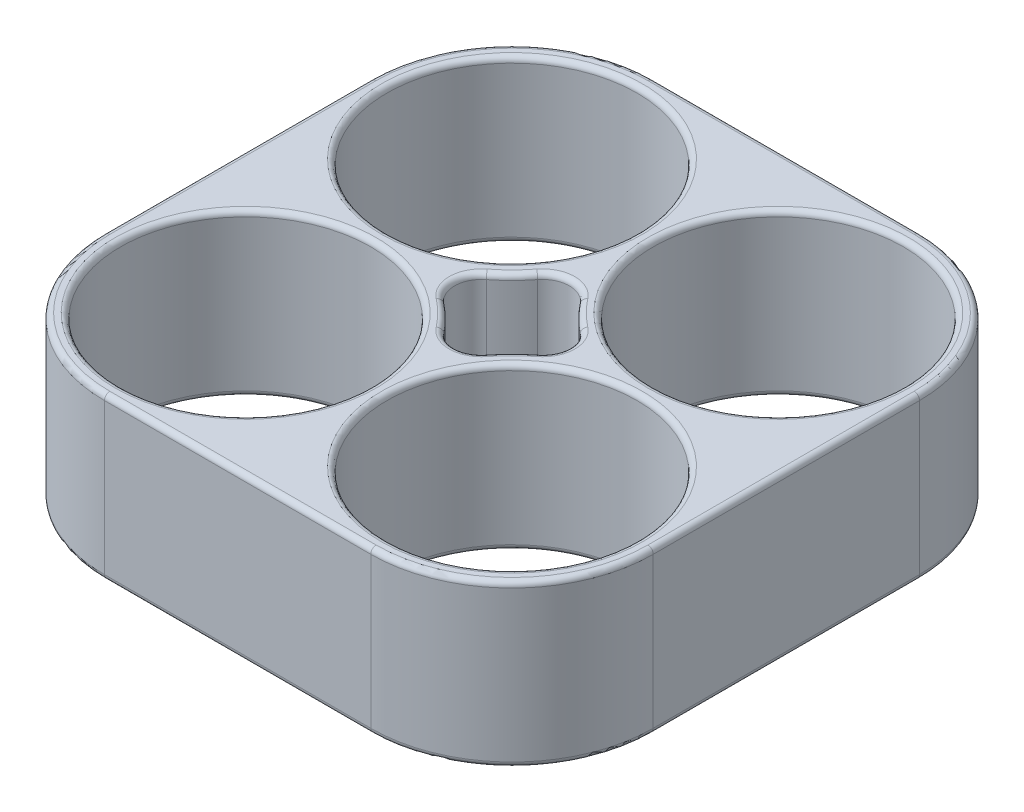
SolidWorks part; units mm, degrees
ref_plane "Front Plane" through (0, 0, 0) normal (0, 0, 1) x (1, 0, 0)
ref_plane "Top Plane" through (0, 0, 0) normal (0, 1, 0) x (1, 0, 0)
ref_plane "Right Plane" through (0, 0, 0) normal (1, 0, 0) x (0, 0, -1)
sketch "Esquisse1" plane through (0, 0, 0) normal (0, 1, 0) x (1, 0, 0)
  line L0 (0, 0) -> (19.8, 0) construction
  line L1 (0, 0) -> (0, 19.8) construction
  line L2 (19.8, 0) -> (19.8, 19.8) construction
  line L3 (-10.5, 19.8) -> (-10.5, 0)
  line L4 (0, 30.3) -> (19.8, 30.3)
  line L5 (30.3, 19.8) -> (30.3, 0)
  line L6 (0, -10.5) -> (19.8, -10.5)
  circle A0 centre (0, 0) radius 9.3
  arc A1 (-10.5, 0) -> (0, -10.5) centre (0, 0) ccw
  circle A2 centre (0, 19.8) radius 9.3
  arc A3 (6.4105, 11.484) -> (8.316, 13.3895) centre (0, 19.8) ccw
  circle A4 centre (19.8, 0) radius 9.3
  arc A5 (13.3895, 8.316) -> (11.484, 6.4105) centre (19.8, 0) ccw
  circle A6 centre (19.8, 19.8) radius 9.3
  arc A7 (30.3, 19.8) -> (19.8, 30.3) centre (19.8, 19.8) ccw
  arc A8 (0, 30.3) -> (-10.5, 19.8) centre (0, 19.8) ccw
  arc A9 (11.484, 13.3895) -> (13.3895, 11.484) centre (19.8, 19.8) ccw
  arc A10 (8.316, 6.4105) -> (6.4105, 8.316) centre (0, 0) ccw
  arc A11 (19.8, -10.5) -> (30.3, 0) centre (19.8, 0) ccw
  arc A12 (6.4105, 11.484) -> (6.4105, 8.316) centre (7.6315, 9.9) ccw
  arc A13 (8.316, 13.3895) -> (11.484, 13.3895) centre (9.9, 12.1685) cw
  arc A14 (13.3895, 11.484) -> (13.3895, 8.316) centre (12.1685, 9.9) cw
  arc A15 (8.316, 6.4105) -> (11.484, 6.4105) centre (9.9, 7.6315) ccw
  dimension "D1" = 18.6
  dimension "D2" = 18.6
  dimension "D3" = 18.6
  dimension "D4" = 18.6
  dimension "D5" = 1.2
  dimension "D6" = 1.2
  dimension "D7" = 1.2
  dimension "D8" = 1.2
  dimension "D9" = 2
extrude "Boss.-Extru.1" add sketch "Esquisse1" along normal blind 12
fillet "Congé1" radius 0.4 40 edges at (19.8, 0, -10.5) (19.8, 0, 9.3) (7.4246, 0, -12.3754) (9.9, 0, -14.1685) (12.3754, 0, -12.3754) (14.1685, 0, -9.9) (12.3754, 0, -7.4246) (9.9, 0, -5.6315) (7.4246, 0, -7.4246) (5.6315, 0, -9.9) (-10.5, 0, -9.9) (-7.4246, 0, 7.4246) (9.9, 0, 10.5) (27.2246, 0, 7.4246) (30.3, 0, -9.9) (27.2246, 0, -27.2246) (9.9, 0, -30.3) (-7.4246, 0, -27.2246) (0, 0, 9.3) (0, 0, -10.5) (19.8, 12, -10.5) (9.9, 12, -5.6315) (12.3754, 12, -7.4246) (14.1685, 12, -9.9) (12.3754, 12, -12.3754) (9.9, 12, -14.1685) (7.4246, 12, -12.3754) (5.6315, 12, -9.9) (7.4246, 12, -7.4246) (0, 12, -10.5) (9.9, 12, -30.3) (27.2246, 12, -27.2246) (30.3, 12, -9.9) (27.2246, 12, 7.4246) (9.9, 12, 10.5) (-7.4246, 12, 7.4246) (-10.5, 12, -9.9) (-7.4246, 12, -27.2246) (0, 12, 9.3) (19.8, 12, 9.3)
